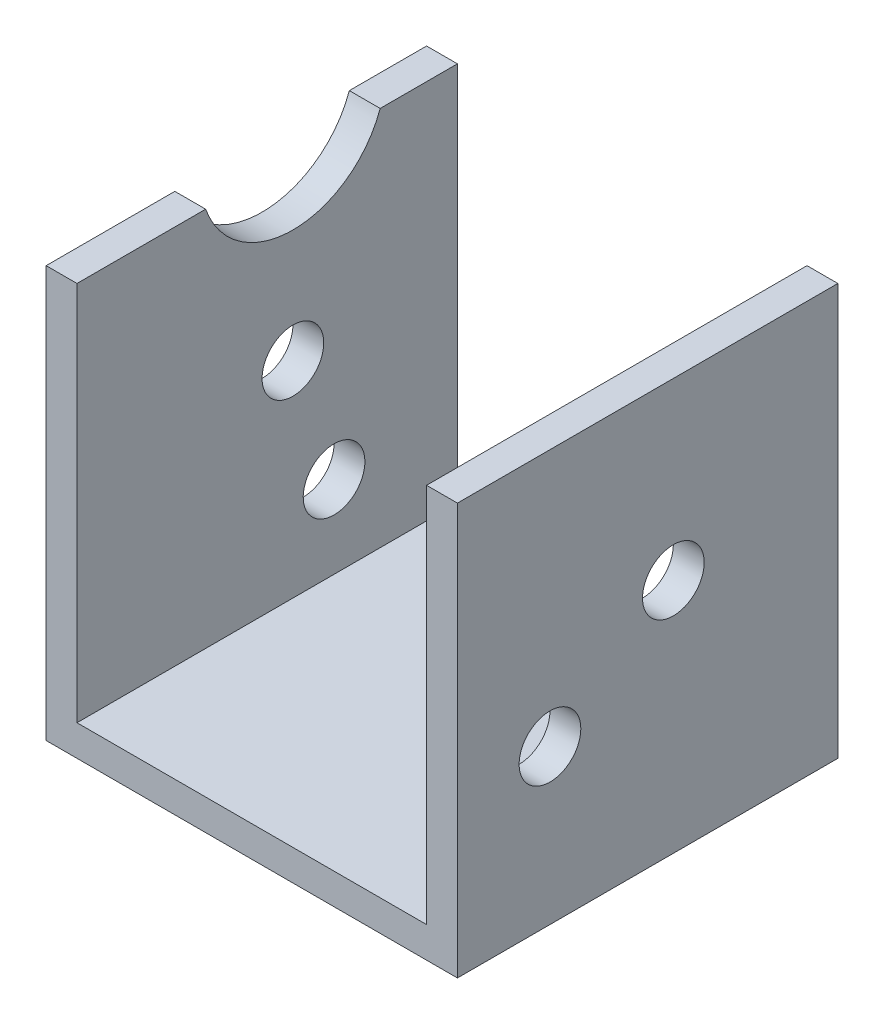
SolidWorks part; units mm, degrees
ref_plane "Plan de face" through (0, 0, 0) normal (0, 0, 1) x (1, 0, 0)
ref_plane "Plan de dessus" through (0, 0, 0) normal (0, 1, 0) x (1, 0, 0)
ref_plane "Plan de droite" through (0, 0, 0) normal (1, 0, 0) x (0, 0, -1)
sketch "Esquisse1" plane through (0, 0, 0) normal (0, 0, 1) x (1, 0, 0)
  line L0 (-16.6363, 18.6356) -> (-16.6363, -1.3644)
  line L1 (-16.6363, -1.3644) -> (3.3637, -1.3644)
  line L2 (3.3637, -1.3644) -> (3.3637, 18.6356)
  line L3 (3.3637, 18.6356) -> (1.8637, 18.6356)
  line L4 (1.8637, 18.6356) -> (1.8637, 0.1356)
  line L5 (1.8637, 0.1356) -> (-15.1363, 0.1356)
  line L6 (-15.1363, 0.1356) -> (-15.1363, 18.6356)
  line L7 (-15.1363, 18.6356) -> (-16.6363, 18.6356)
  dimension "D1" = 1.5
  dimension "D2" = 1.5
  dimension "D3" = 1.5
  dimension "D4" = 20
  dimension "D5" = 20
  dimension "D6" = 20
extrude "Extrusion1" add sketch "Esquisse1" along normal blind 18.5
sketch "Esquisse2" plane through (3.3637, 0, 0) normal (1, 0, 0) x (0, 0, -1)
  line L0 (-18.5, -1.3644) -> (0, -1.3644) construction
  line L2 (-18.5, -1.3644) -> (-18.5, 18.6356) construction
  circle A0 centre (-14, 6.1356) radius 1.5
  dimension "D1" = 7.5
  dimension "D2" = 4.5
extrude "Extrusion2" cut sketch "Esquisse2" against normal blind 5
sketch "Esquisse3" plane through (-16.6363, 0, 0) normal (-1, 0, 0) x (0, 0, 1)
  line L0 (18.5, 18.6356) -> (0, 18.6356) construction
  line L1 (0, 18.6356) -> (0, -1.3644) construction
  line L2 (18.5, -1.3644) -> (0, -1.3644) construction
  circle A0 centre (8, 20.1356) radius 4.5
  circle A1 centre (6, 4.1356) radius 1.5
  point P4 (9.25, 18.6356)
  point P10 (-30.9175, 17.1618)
  dimension "D1" = 8
  dimension "D3" = 6
  dimension "D2" = 1.5
  dimension "D4" = 5.5
extrude "Extrusion3" cut sketch "Esquisse3" against normal blind 5
sketch "Esquisse4" plane through (-16.6363, 0, 0) normal (-1, 0, 0) x (0, 0, 1)
  line L0 (0, 18.6356) -> (0, -1.3644) construction
  line L1 (18.5, -1.3644) -> (0, -1.3644) construction
  circle A0 centre (8, 10.1356) radius 1.5
  dimension "D1" = 8
  dimension "D2" = 11.5
extrude "Extrusion4" cut sketch "Esquisse4" against normal through all
